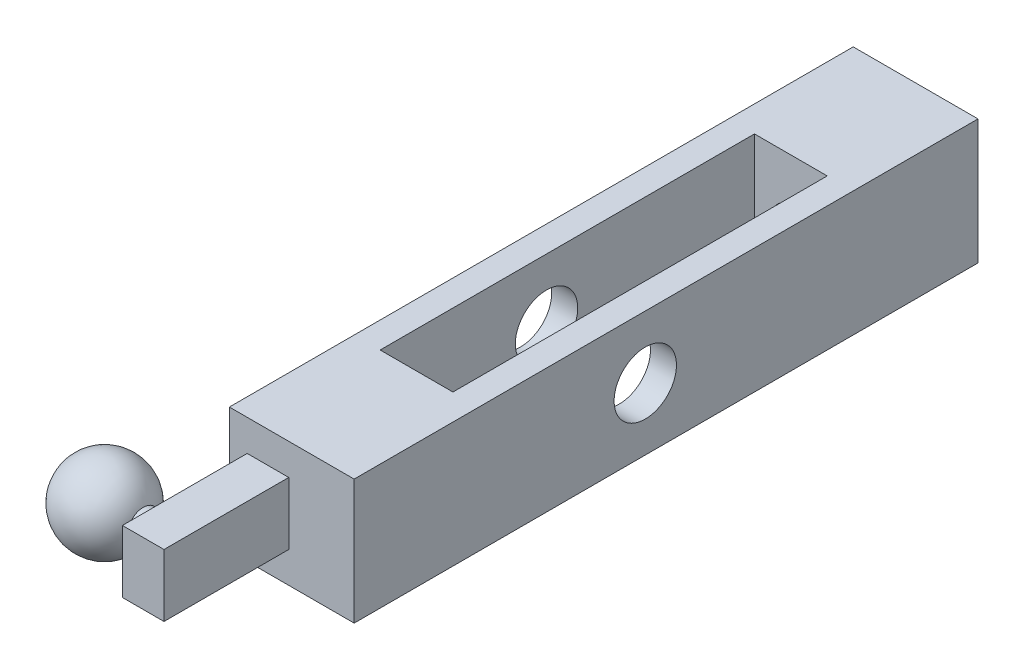
SolidWorks part; units mm, degrees
ref_plane "前视基准面" through (0, 0, 0) normal (0, 0, 1) x (1, 0, 0)
ref_plane "上视基准面" through (0, 0, 0) normal (0, 1, 0) x (1, 0, 0)
ref_plane "右视基准面" through (0, 0, 0) normal (1, 0, 0) x (0, 0, -1)
other "Configuration Table"
sketch "草图1" plane through (0, 0, 0) normal (0, 0, 1) x (1, 0, 0)
  line L1 (3, -3) -> (-3, -3)
  line L2 (3, -3) -> (3, 3)
  line L3 (3, 3) -> (-3, 3)
  line L4 (-3, -3) -> (-3, 3)
  line L5 (3, -3) -> (-3, 3) construction
  line L6 (3, 3) -> (-3, -3) construction
  point P0 (0, 0)
  dimension "D1" = 6
  dimension "D2" = 6
extrude "凸台-拉伸1" add sketch "草图1" along normal blind 30
sketch "草图2" plane through (0, 0, 30) normal (0, 0, 1) x (1, 0, 0)
  line L1 (-2.1448, 1.4955) -> (-0.1448, 1.4955)
  line L2 (-2.1448, 1.4955) -> (-2.1448, -1.5045)
  line L3 (-2.1448, -1.5045) -> (-0.1448, -1.5045)
  line L4 (-0.1448, 1.4955) -> (-0.1448, -1.5045)
  line L5 (-2.1448, 1.4955) -> (-0.1448, -1.5045) construction
  line L6 (-2.1448, -1.5045) -> (-0.1448, 1.4955) construction
  point P0 (-1.1448, -0.0045)
  dimension "D1" = 2
  dimension "D2" = 3
extrude "凸台-拉伸2" add sketch "草图2" along normal blind 6
sketch "草图3" plane through (-2.1448, 0, 0) normal (-1, 0, 0) x (0, 0, 1)
  circle A0 centre (34, 0) radius 0.75
  dimension "D1" = 1.5
  dimension "D2" = 34
extrude "凸台-拉伸3" add sketch "草图3" along normal blind 1
sketch "草图4" plane through (0, 0, 0) normal (0, 1, 0) x (1, 0, 0)
  line L0 (-3.1448, -34) -> (-6.9988, -34)
  line L1 (-3.1448, -33.25) -> (-3.1448, -34.75) construction
  line L2 (-3.1448, -34) -> (-3.1448, -33.25)
  arc A0 (-3.1448, -33.25) -> (-6.9988, -34) centre (-4.9988, -34) ccw
  dimension "D1" = 4
revolve "旋转1" add sketch "草图4" angle 360 about L0
sketch "草图5" plane through (0.5, 3, 0) normal (0, -1, 0) x (0, 0, 1)
  line L0 (30, 3.5) -> (0, 3.5) construction
  line L1 (6, 2.25) -> (24, 2.25)
  line L2 (6, 2.25) -> (6, -1.25)
  line L3 (6, -1.25) -> (24, -1.25)
  line L4 (24, 2.25) -> (24, -1.25)
  point P4 (6, 0.5)
  point P8 (15, 3.5)
  point P9 (15, 2.25)
  dimension "D1" = 18
  dimension "D2" = 3.5
extrude "切除-拉伸1" cut sketch "草图5" along normal blind 8
sketch "草图6" plane through (-3, 0, 0) normal (-1, 0, 0) x (0, 0, 1)
  line L0 (0, 3) -> (0, -3) construction
  circle A0 centre (16, 0) radius 1.5
  dimension "D1" = 3
  dimension "D2" = 16
extrude "切除-拉伸2" cut sketch "草图6" against normal blind 8
sketch "草图7" plane through (0, 0, 0) normal (0, 0, -1) x (-1, 0, 0)
  circle A0 centre (0, 0) radius 0.9
  dimension "D1" = 1.8
extrude "切除-拉伸3" cut sketch "草图7" against normal blind 8
